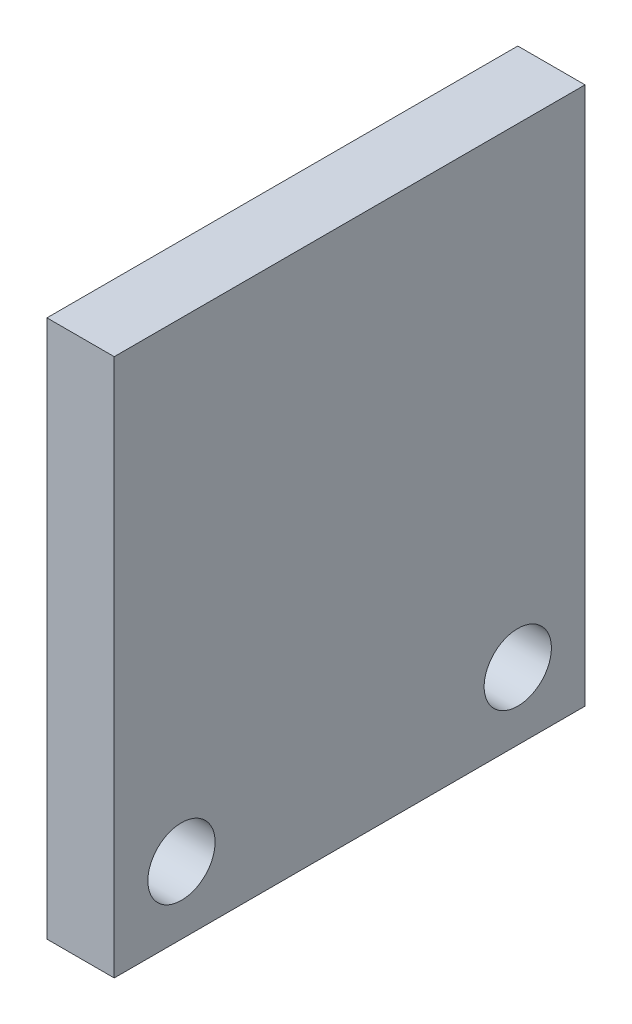
SolidWorks part; units mm, degrees
ref_plane "Front Plane" through (0, 0, 0) normal (0, 0, 1) x (1, 0, 0)
ref_plane "Top Plane" through (0, 0, 0) normal (0, 1, 0) x (1, 0, 0)
ref_plane "Right Plane" through (0, 0, 0) normal (1, 0, 0) x (0, 0, -1)
sketch "Sketch1" plane through (0, 0, 0) normal (1, 0, 0) x (0, 0, -1)
  line L1 (-17.5, 20) -> (17.5, 20)
  line L2 (-17.5, 20) -> (-17.5, -20)
  line L3 (-17.5, -20) -> (17.5, -20)
  line L4 (17.5, 20) -> (17.5, -20)
  line L5 (-17.5, 20) -> (17.5, -20) construction
  line L6 (-17.5, -20) -> (17.5, 20) construction
  point P0 (0, 0)
  dimension "D1" = 35
  dimension "D2" = 40
extrude "Boss-Extrude1" add sketch "Sketch1" along normal blind 5
sketch "Sketch2" plane through (5, 0, 0) normal (1, 0, 0) x (0, 0, -1)
  line L0 (-17.5, 20) -> (-17.5, -20) construction
  line L1 (-17.5, -20) -> (17.5, -20) construction
  line L2 (17.5, -20) -> (17.5, 20) construction
  circle A0 centre (-12.5, -15) radius 2.5
  circle A1 centre (12.5, -15) radius 2.5
  point P4 (6.4365, -9.9297)
  dimension "D1" = 5
  dimension "D2" = 5
  dimension "D3" = 5
  dimension "D4" = 5
extrude "Cut-Extrude1" cut sketch "Sketch2" against normal through all
